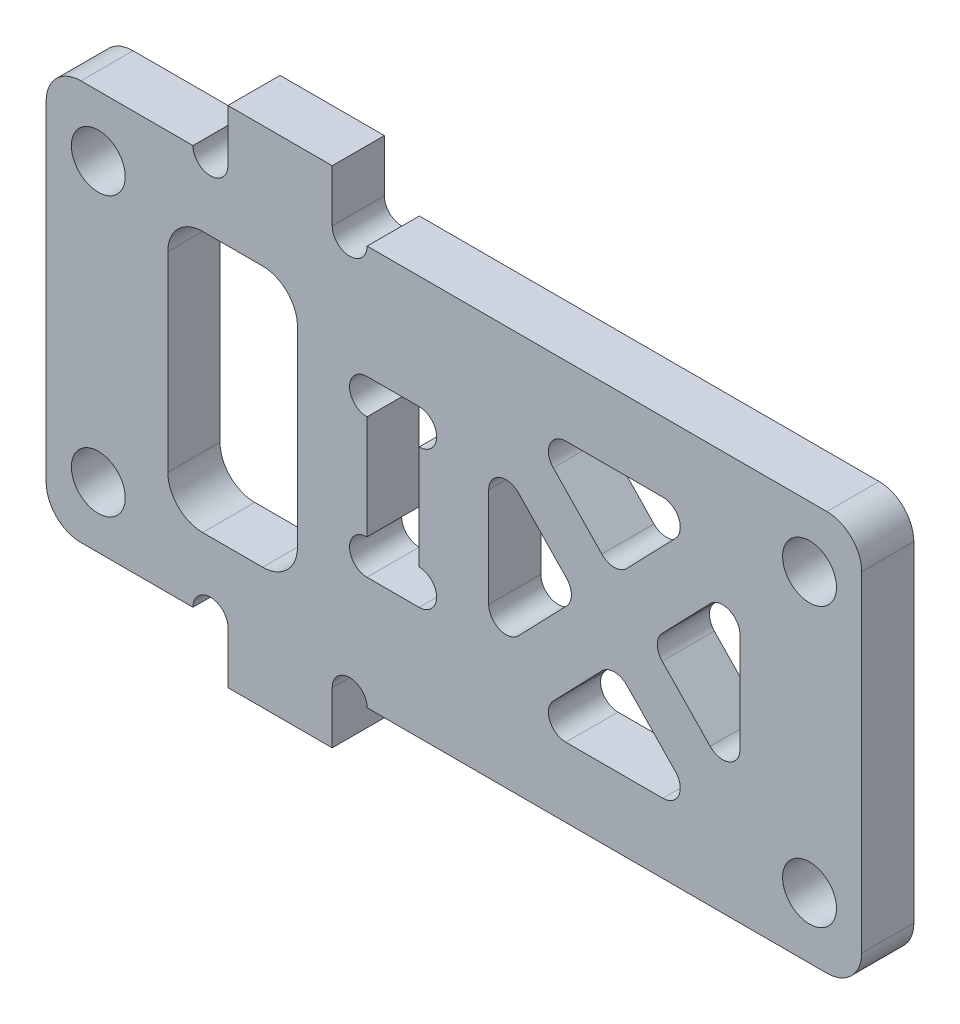
SolidWorks part; units mm, degrees
material "Thornel Mat VMA"
ref_plane "前视基准面" through (0, 0, 0) normal (0, 0, 1) x (1, 0, 0)
ref_plane "上视基准面" through (0, 0, 0) normal (0, 1, 0) x (1, 0, 0)
ref_plane "右视基准面" through (0, 0, 0) normal (1, 0, 0) x (0, 0, -1)
sketch "草图1" plane through (0, 0, 0) normal (0, 0, 1) x (1, 0, 0)
  line L0 (-13, 11.5) -> (-13, 14.5)
  line L1 (23.455, -11.5) -> (-7, -11.5)
  line L2 (23.455, -11.5) -> (23.455, 11.5)
  line L3 (23.455, 11.5) -> (-7, 11.5)
  line L4 (-23.455, -11.5) -> (-23.455, 11.5)
  line L5 (23.455, -11.5) -> (-23.455, 11.5) construction
  line L6 (23.455, 11.5) -> (-23.455, -11.5) construction
  line L7 (-20.455, 8) -> (-20.455, -8) construction
  line L8 (-20.455, 0) -> (0, 0) construction
  line L9 (0, 0) -> (0, 8.6559) construction
  line L10 (-2, -5) -> (-5, -5)
  line L11 (-2, -5) -> (-2, 5)
  line L12 (-2, 5) -> (-5, 5)
  line L13 (-5, -5) -> (-5, 5)
  line L14 (-2, -5) -> (-5, 5) construction
  line L15 (-2, 5) -> (-5, -5) construction
  line L16 (-13, 14.5) -> (-7, 14.5)
  line L17 (-7, 14.5) -> (-7, 11.5)
  line L18 (-13, 11.5) -> (-23.455, 11.5)
  line L19 (-7, -14.5) -> (-7, -11.5)
  line L20 (-13, -14.5) -> (-7, -14.5)
  line L21 (-13, -11.5) -> (-13, -14.5)
  line L22 (-13, -11.5) -> (-23.455, -11.5)
  line L23 (14.3719, -7.5) -> (9.2275, -2.1617)
  line L28 (-9, 7.5) -> (-16.455, 7.5)
  line L29 (-9, 7.5) -> (-9, -7.5)
  line L30 (14.3719, 7.5) -> (4.0831, 7.5)
  line L31 (16.455, 5.3383) -> (16.455, -5.3383)
  line L32 (14.3719, -7.5) -> (4.0831, -7.5)
  line L33 (2, 5.3383) -> (2, -5.3383)
  line L34 (16.455, 7.5) -> (2, -7.5) construction
  line L35 (16.455, -7.5) -> (2, 7.5) construction
  line L36 (-9, -7.5) -> (-16.455, -7.5)
  line L37 (-16.455, 7.5) -> (-16.455, -7.5)
  line L38 (-9, 7.5) -> (-16.455, -7.5) construction
  line L39 (-9, -7.5) -> (-16.455, 7.5) construction
  line L40 (16.455, -5.3383) -> (11.3106, 0)
  line L41 (2, -5.3383) -> (7.1444, 0)
  line L42 (4.0831, -7.5) -> (9.2275, -2.1617)
  line L43 (7.1444, 0) -> (2, 5.3383)
  line L44 (9.2275, 2.1617) -> (4.0831, 7.5)
  line L45 (11.3106, 0) -> (16.455, 5.3383)
  line L46 (9.2275, 2.1617) -> (14.3719, 7.5)
  circle A0 centre (-20.455, 8) radius 1.55
  circle A1 centre (-20.455, -8) radius 1.55
  circle A4 centre (20.455, -8) radius 1.55
  circle A5 centre (20.455, 8) radius 1.55
  circle A6 centre (-2, 3.995) radius 1.005
  circle A7 centre (-5, 3.995) radius 1.005
  circle A8 centre (-5, -3.995) radius 1.005
  circle A9 centre (-2, -3.995) radius 1.005
  circle A10 centre (-5.995, 11.5) radius 1.005
  circle A11 centre (-14.005, 11.5) radius 1.005
  circle A12 centre (-5.995, -11.5) radius 1.005
  circle A13 centre (-14.005, -11.5) radius 1.005
  point P0 (0, 0)
  point P7 (-3.5, 0)
  point P46 (-12.7275, 0)
  point P51 (9.2275, 0)
  dimension "D1" = 3.1
  dimension "D9" = 2.01
  dimension "D2" = 16
  dimension "D3" = 23
  dimension "D4" = 3
  dimension "D5" = 3
  dimension "D6" = 2
  dimension "D7" = 10
  dimension "D8" = 40.91
  dimension "D10" = 6
  dimension "D11" = 2
  dimension "D12" = 3
  dimension "D13" = 4
  dimension "D14" = 4
  dimension "D15" = 4
  dimension "D16" = 4
  dimension "D17" = 4
  dimension "D18" = 1.5
  dimension "D19" = 3
  dimension "D20" = 1.5
  dimension "D21" = 3
extrude "凸台-拉伸1" add sketch "草图1" along normal blind 3 contours A11 L18 L4 L1 L2 L3 A10 L17 L16 L0 A9 L10 A8 L13 A7 L12 A6 L11 A4 A1 A0 A5
fillet "圆角1" radius 2 8 edges at (23.455, -11.5, 1.5) (23.455, 11.5, 1.5) (-23.455, 11.5, 1.5) (-23.455, -11.5, 1.5) (-16.455, 7.5, 1.5) (-9, 7.5, 1.5) (-9, -7.5, 1.5) (-16.455, -7.5, 1.5)
fillet "圆角2" radius 1 12 edges at (14.3719, 7.5, 1.5) (4.0831, 7.5, 1.5) (9.2275, 2.1617, 1.5) (2, 5.3383, 1.5) (2, -5.3383, 1.5) (7.1444, 0, 1.5) (14.3719, -7.5, 1.5) (9.2275, -2.1617, 1.5) (16.455, -5.3383, 1.5) (16.455, 5.3383, 1.5) (11.3106, 0, 1.5) (4.0831, -7.5, 1.5)
